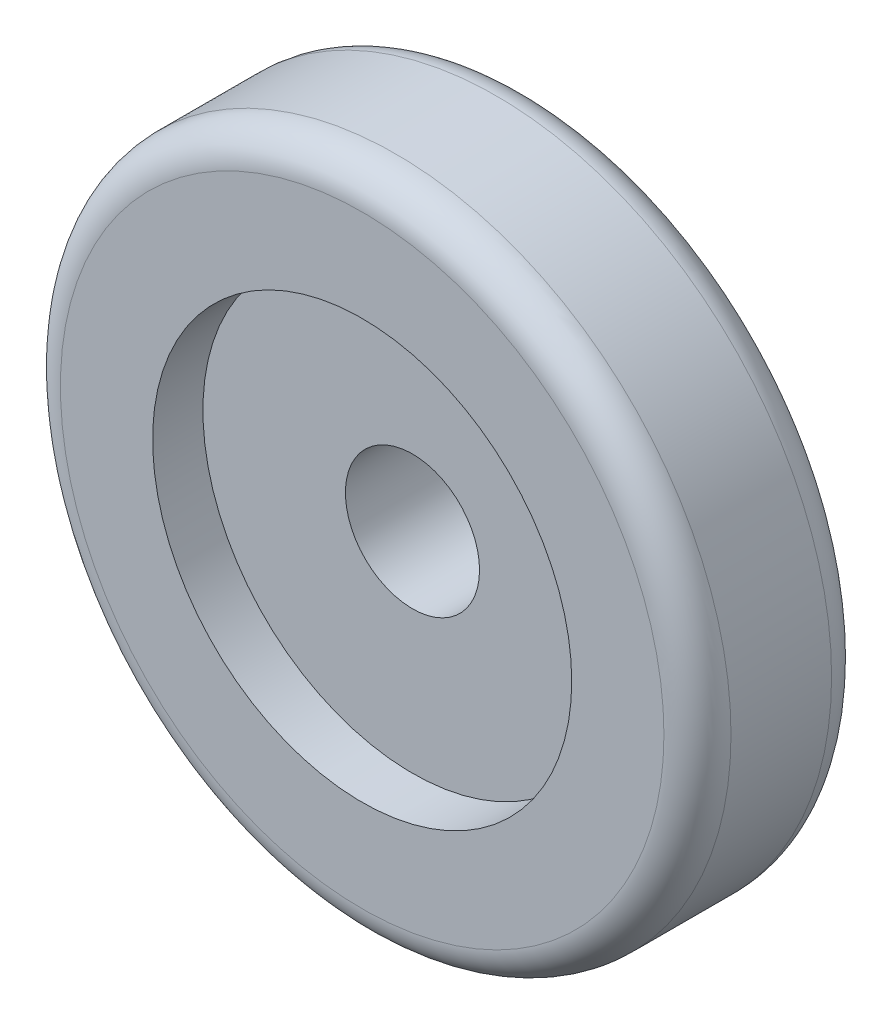
SolidWorks part; units mm, degrees
material "Teak"
ref_plane "Plano frontal" through (0, 0, 0) normal (0, 0, 1) x (1, 0, 0)
ref_plane "Plano superior" through (0, 0, 0) normal (0, 1, 0) x (1, 0, 0)
ref_plane "Plano direito" through (0, 0, 0) normal (1, 0, 0) x (0, 0, -1)
sketch "Sketch1" plane through (0, 0, 0) normal (0, 0, 1) x (1, 0, 0)
  circle A0 centre (0, 0) radius 20
  dimension "D1" = 40
extrude "Boss-Extrude1" add sketch "Sketch1" along normal blind 10
sketch "Sketch2" plane through (0, 0, 10) normal (0, 0, 1) x (1, 0, 0)
  circle A0 centre (0, 0) radius 4
  dimension "D1" = 8
extrude "Cut-Extrude1" cut sketch "Sketch2" against normal through all
sketch "Sketch3" plane through (0, 0, 10) normal (0, 0, 1) x (1, 0, 0)
  circle A0 centre (0, 0) radius 12.5
  dimension "D1" = 25
extrude "Cut-Extrude2" cut sketch "Sketch3" against normal blind 3
fillet "Fillet1" radius 2 2 edges at (20, 0, 0) (20, 0, 10)
